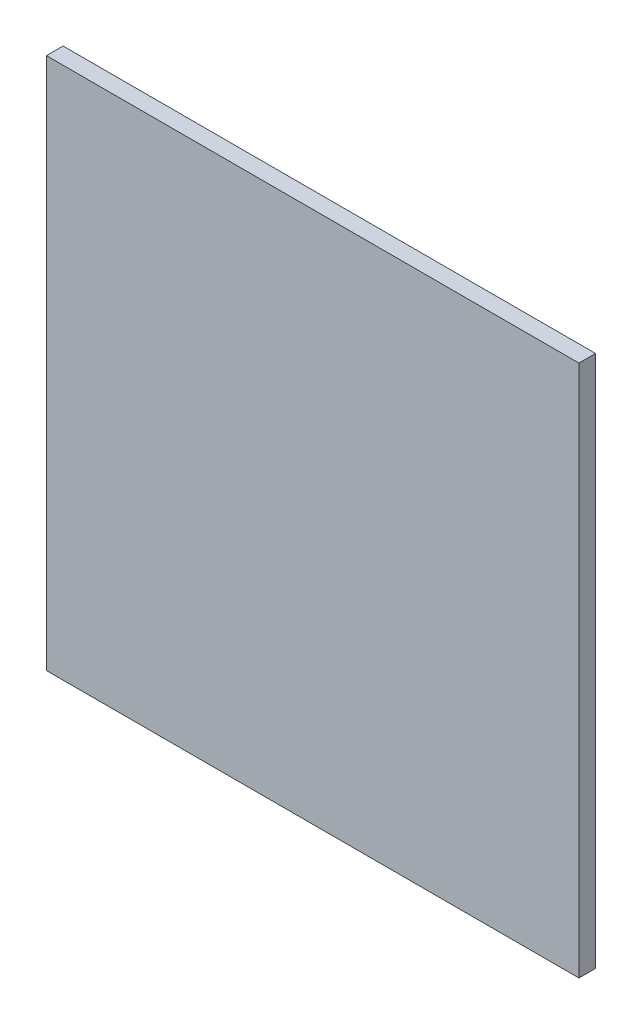
SolidWorks part; units mm, degrees
material "Maple"
ref_plane "Front Plane" through (0, 0, 0) normal (0, 0, 1) x (1, 0, 0)
ref_plane "Top Plane" through (0, 0, 0) normal (0, 1, 0) x (1, 0, 0)
ref_plane "Right Plane" through (0, 0, 0) normal (1, 0, 0) x (0, 0, -1)
sketch "Sketch1" plane through (0, 0, 0) normal (0, 0, 1) x (1, 0, 0)
  line L0 (609.8, 304.8) -> (609.6, 304.8) construction
  line L1 (0, 0) -> (609.6, 0)
  line L2 (0, 0) -> (0, 609.6)
  line L3 (0, 609.6) -> (609.6, 609.6)
  line L4 (609.6, 0) -> (609.6, 609.6)
  line L5 (-0.2, 569.8) -> (609.8, 569.8) construction
  line L6 (-0.2, 569.8) -> (-0.2, 39.8) construction
  line L7 (-0.2, 39.8) -> (609.8, 39.8) construction
  line L8 (609.8, 569.8) -> (609.8, 39.8) construction
  line L9 (0, 304.8) -> (-0.2, 304.8) construction
  line L10 (304.8, 609.6) -> (304.8, 569.8) construction
  line L11 (304.8, 0) -> (304.8, 39.8) construction
  dimension "D1" = 609.6
  dimension "D2" = 609.6
  dimension "D3" = 610
  dimension "D4" = 530
extrude "Boss-Extrude1" add sketch "Sketch1" along normal blind 19.05 contours L8 L5 L2 L7
